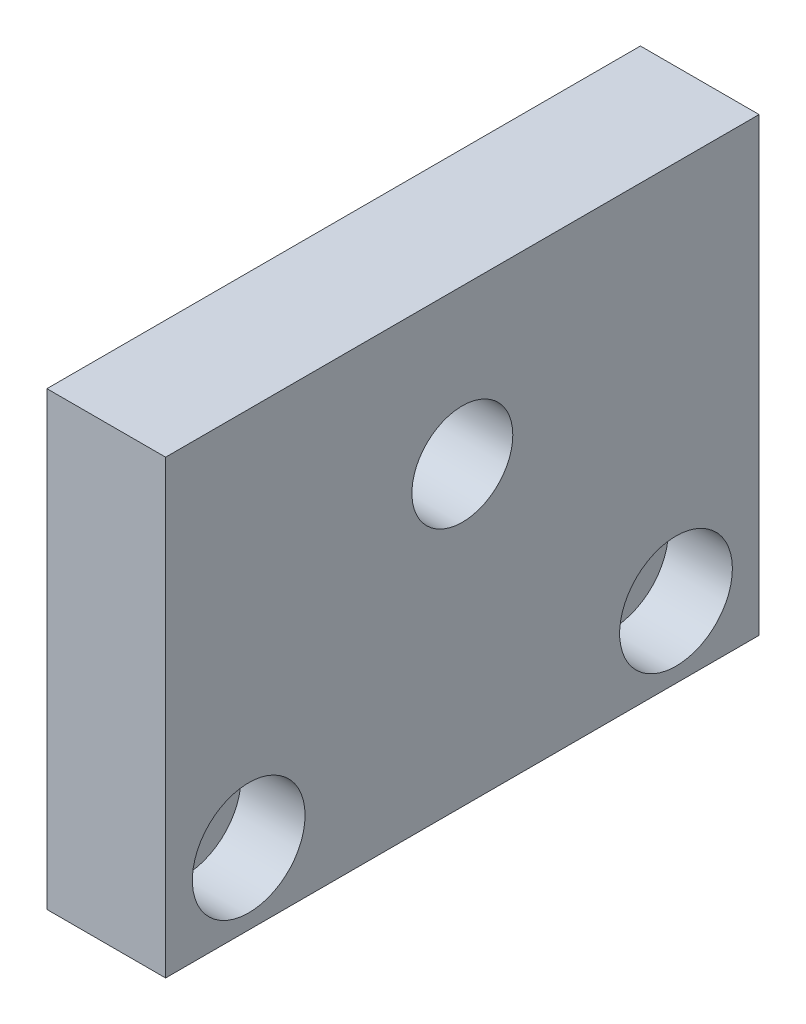
SolidWorks part; units mm, degrees
ref_plane "Front" through (0, 0, 0) normal (0, 0, 1) x (1, 0, 0)
ref_plane "Top" through (0, 0, 0) normal (0, 1, 0) x (1, 0, 0)
ref_plane "Right" through (0, 0, 0) normal (1, 0, 0) x (0, 0, -1)
sketch "Sketch1" plane through (0, 0, 0) normal (1, 0, 0) x (0, 0, -1)
  line L0 (0, -7.004) -> (0, 48.1523) construction
  line L1 (-25, 38) -> (25, 38)
  line L2 (-25, 38) -> (-25, 0)
  line L3 (-25, 0) -> (25, 0)
  line L4 (25, 38) -> (25, 0)
  dimension "D1" = 50
  dimension "D2" = 38
extrude "Boss-Extrude1" add sketch "Sketch1" along normal blind 10
hole_wizard "M10x1.5 Tapped Hole1" positions "Sketch3" profile "Sketch2" tap size "M10x1.5" standard "JIS" end condition through all
sketch "Sketch3" plane through (10, 0, 0) normal (1, 0, 0) x (0, 0, -1)
  line L0 (-25, 0) -> (25, 0) construction
  point P0 (0, 25)
  dimension "D1" = 25
sketch "Sketch2" plane through (10, 25, 0) normal (0, 1, 0) x (0, 0, -1)
  line L0 (0, 0) -> (0, 10)
  line L1 (0, 10) -> (4.25, 10)
  line L2 (4.25, 10) -> (4.25, 0)
  line L5 (4.25, 0) -> (0, 0)
  line L11 (0, -6.35) -> (0, 107.95) construction
  dimension "Thru Tap Drill Dia." = 8.5
  dimension "Thru Tap Drill Depth" = 10
cosmetic thread "Hole Thread1" parameters "D2"=10
hole_wizard "CBORE for M5 Socket Head Cap Screw1" positions "Sketch5" profile "Sketch4" counterbore size "M5" standard "JIS" end condition through all
sketch "Sketch5" plane through (10, 0, 0) normal (1, 0, 0) x (0, 0, -1)
  line L0 (0, -2.6587) -> (0, 41.9822) construction
  line L1 (-25, 0) -> (25, 0) construction
  point P0 (18, 6)
  point P1 (-18, 6)
  dimension "D1" = 36
  dimension "D2" = 6
sketch "Sketch4" plane through (10, 6, -18) normal (0, 1, 0) x (0, 0, -1)
  line L0 (0, 0) -> (0, 10)
  line L1 (0, 10) -> (2.75, 10)
  line L3 (2.75, 10) -> (2.75, 5.4)
  line L4 (2.75, 5.4) -> (4.75, 5.4)
  line L5 (4.75, 5.4) -> (4.75, 0)
  line L7 (4.75, 0) -> (0, 0)
  line L11 (0, -6.35) -> (0, 107.95) construction
  dimension "Thru Hole Dia." = 5.5
  dimension "Thru Hole Depth" = 10
  dimension "C'Bore Dia." = 9.5
  dimension "C'Bore Depth" = 5.4
